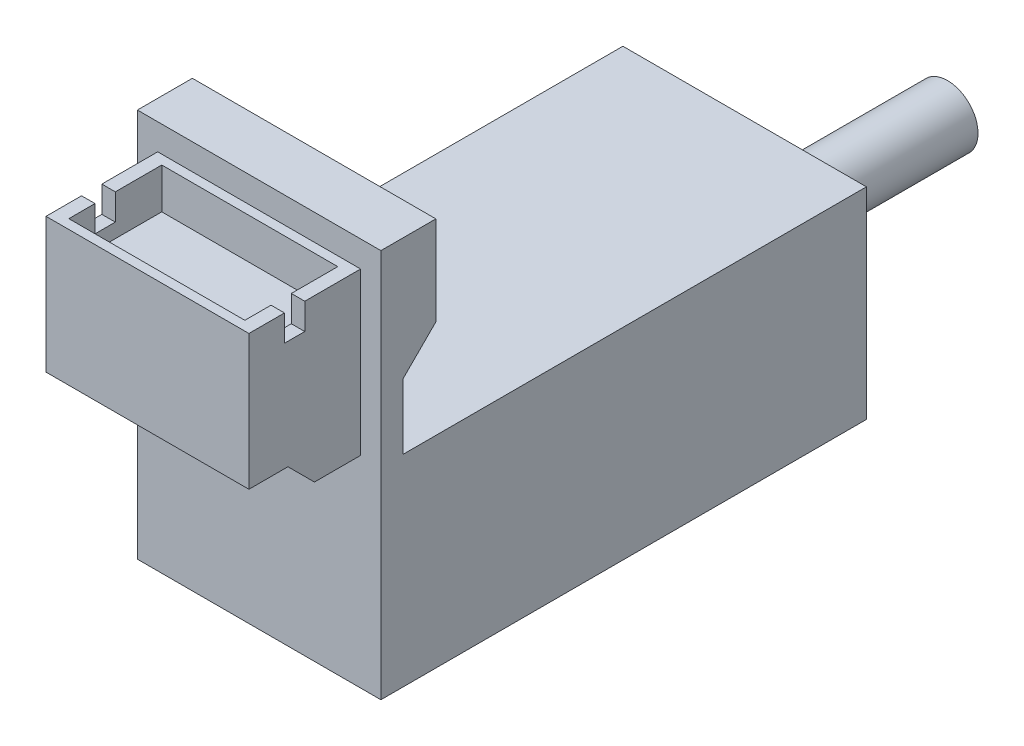
SolidWorks part; units mm, degrees
ref_plane "Front Plane" through (0, 0, 0) normal (0, 0, 1) x (1, 0, 0)
ref_plane "Top Plane" through (0, 0, 0) normal (0, 1, 0) x (1, 0, 0)
ref_plane "Right Plane" through (0, 0, 0) normal (1, 0, 0) x (0, 0, -1)
sketch "Sketch1" plane through (0, 0, 0) normal (1, 0, 0) x (0, 0, -1)
  line L0 (7.576, 4.965) -> (-6.4629, 4.965)
  line L3 (-7.55, -4.965) -> (7.55, -4.965)
  line L6 (7.576, 4.965) -> (16.376, 4.965)
  line L11 (16.376, 4.965) -> (16.376, -4.965)
  line L12 (16.376, -4.965) -> (7.55, -4.965)
  line L13 (-6.4629, 4.965) -> (-6.4629, 8.1873)
  line L14 (-6.4629, 8.1873) -> (-4.8409, 9.8093)
  line L15 (-4.8409, 9.8093) -> (-4.8409, 14.205)
  line L16 (-4.8409, 14.205) -> (-7.55, 14.205)
  line L17 (-7.55, -4.965) -> (-7.55, 4.965)
  line L19 (-7.55, 4.965) -> (-9.8251, 4.965)
  line L20 (-13.054, 12.921) -> (-7.55, 12.921)
  line L21 (-7.55, 14.205) -> (-7.55, 12.921)
  line L22 (-9.8251, 4.965) -> (-11.131, 6.2708)
  line L23 (-11.131, 6.2708) -> (-13.054, 6.2708)
  line L24 (-13.054, 6.2708) -> (-13.054, 12.921)
  point P0 (0, 0)
  dimension "D1" = 15.1
  dimension "D2" = 8.8
  dimension "D3" = 29.43
  dimension "D4" = 19.17
  dimension "D6" = 9.93
extrude "Boss-Extrude2" add sketch "Sketch1" along normal blind 12
sketch "Sketch2" plane through (0, 0, -16.376) normal (0, 0, -1) x (-1, 0, 0)
  line L0 (-12, -4.965) -> (0, -4.965) construction
  line L1 (0, -4.965) -> (0, 4.965) construction
  circle A0 centre (-6, 0) radius 2
  dimension "D1" = 4.965
  dimension "D2" = 6
  dimension "D3" = 4
extrude "Boss-Extrude3" add sketch "Sketch2" along normal blind 1
sketch "Sketch3" plane through (0, 0, -17.376) normal (0, 0, -1) x (-1, 0, 0)
  circle A0 centre (-6, 0) radius 1.5
  dimension "D1" = 3
extrude "Boss-Extrude4" add sketch "Sketch3" along normal blind 9 contours A0
sketch "Sketch4" plane through (0, 0, -26.376) normal (0, 0, -1) x (-1, 0, 0)
  line L0 (-6.8398, -1.2428) -> (-5.1602, -1.2428)
  circle A3 centre (-6, 0) radius 1.5 construction
  circle A4 centre (-6, 0) radius 1.5 construction
  arc A6 (-6.8398, -1.2428) -> (-5.1602, -1.2428) centre (-6, 0) ccw
  point P9 (-6, -1.2428)
extrude "Cut-Extrude1" cut sketch "Sketch4" against normal blind 9
sketch "Sketch5" plane through (0, 12.921, 0) normal (0, 1, 0) x (1, 0, 0)
  line L0 (12, -7.55) -> (11, -7.55)
  line L1 (12, -7.55) -> (0, -7.55) construction
  line L2 (11, -7.55) -> (11, -13.054)
  line L3 (12, -13.054) -> (0, -13.054) construction
  line L4 (11, -13.054) -> (12, -13.054)
  line L5 (12, -13.054) -> (12, -7.55)
  line L6 (0, -7.55) -> (0, -13.054)
  line L7 (0, -13.054) -> (1, -13.054)
  line L8 (1, -13.054) -> (1, -7.55)
  line L9 (12, -7.55) -> (0, -7.55) construction
  line L10 (1, -7.55) -> (0, -7.55)
  dimension "D1" = 1
  dimension "D2" = 1
extrude "Cut-Extrude2" cut sketch "Sketch5" against normal through all
sketch "Sketch6" plane through (11, 0, 0) normal (1, 0, 0) x (0, 0, -1)
  line L0 (-11.302, 12.921) -> (-11.302, 11.6277)
  line L1 (-7.55, 12.921) -> (-13.054, 12.921) construction
  line L2 (-11.302, 11.6277) -> (-10.302, 11.6277)
  line L3 (-10.302, 11.6277) -> (-10.302, 12.921)
  line L4 (-10.302, 12.921) -> (-11.302, 12.921)
  dimension "D1" = 1
extrude "Cut-Extrude3" cut sketch "Sketch6" against normal through all
sketch "Sketch7" plane through (0, 12.921, 0) normal (0, 1, 0) x (1, 0, 0)
  line L0 (1, -10.302) -> (11, -10.302) construction
  line L1 (1.6626, -8.0117) -> (10.3374, -8.0117)
  line L2 (1.6626, -8.0117) -> (1.6626, -12.5923)
  line L3 (1.6626, -12.5923) -> (10.3374, -12.5923)
  line L4 (10.3374, -8.0117) -> (10.3374, -12.5923)
  line L5 (1.6626, -8.0117) -> (10.3374, -12.5923) construction
  line L6 (1.6626, -12.5923) -> (10.3374, -8.0117) construction
  point P0 (6, -10.302)
extrude "Cut-Extrude4" cut sketch "Sketch7" against normal blind 2
